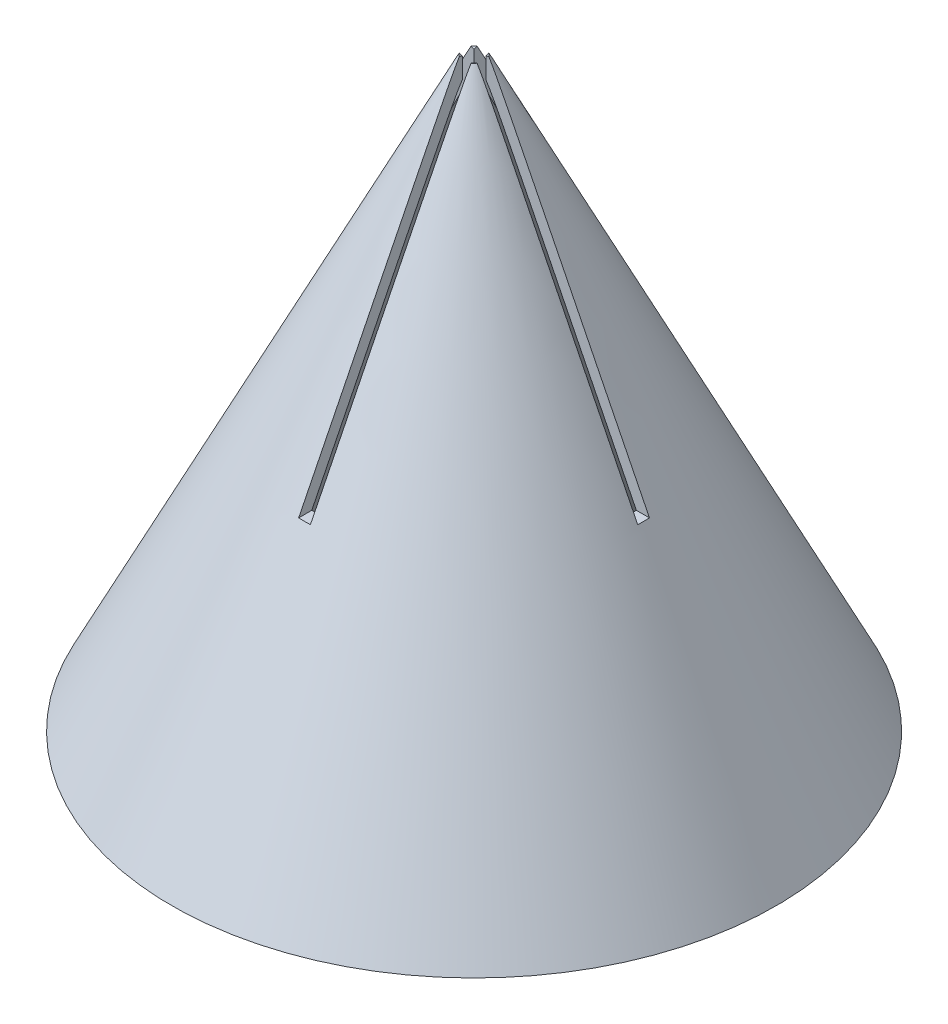
SolidWorks part; units mm, degrees
material "Thornel VCB-20 Carbon Cloth"
ref_plane "Front Plane" through (0, 0, 0) normal (0, 0, 1) x (1, 0, 0)
ref_plane "Top Plane" through (0, 0, 0) normal (0, 1, 0) x (1, 0, 0)
ref_plane "Right Plane" through (0, 0, 0) normal (1, 0, 0) x (0, 0, -1)
sketch "Sketch1" plane through (0, 0, 0) normal (0, 0, 1) x (1, 0, 0)
  line L1 (-22.25, 0.3849) -> (-0.7831, 43.5)
  line L4 (-0.7831, 43.5) -> (-0.01, 43.1151)
  line L5 (-0.01, 43.1151) -> (-21.4769, 0)
  line L6 (0, 0) -> (0, 9.1947) construction
  line L7 (-22.25, 0.3849) -> (-21.4769, 0)
  point P5 (0, 0)
  dimension "D1" = 0.8636
  dimension "D2" = 43.5
  dimension "D3" = 22.25
  dimension "D4" = 0.01
revolve "Revolve1" add sketch "Sketch1" angle 360 about L6
ref_plane "Plane1" through (0, 43.5, 0) normal (0, -1, 0) x (-1, 0, 0)
sketch "Sketch3" plane through (0, 43.5, 0) normal (0, -1, 0) x (-1, 0, 0)
  line L0 (-20.4318, -0.4318) -> (-20.4318, 0.4318)
  line L1 (-20.4318, 0.4318) -> (-0.4318, 0.4318)
  line L2 (-0.4318, 0.4318) -> (-0.4318, 20.4318)
  line L3 (-0.4318, 20.4318) -> (0.4318, 20.4318)
  line L4 (0.4318, 20.4318) -> (0.4318, 0.4318)
  line L5 (0.4318, 0.4318) -> (20.4318, 0.4318)
  line L6 (20.4318, 0.4318) -> (20.4318, -0.4318)
  line L7 (20.4318, -0.4318) -> (0.4318, -0.4318)
  line L8 (0.4318, -0.4318) -> (0.4318, -20.4318)
  line L9 (0.4318, -20.4318) -> (-0.4318, -20.4318)
  line L10 (-0.4318, -20.4318) -> (-0.4318, -0.4318)
  line L11 (-0.4318, -0.4318) -> (-20.4318, -0.4318)
  line L12 (-0.4318, -0.4318) -> (0.4318, 0.4318) construction
  line L13 (0.4318, -0.4318) -> (-0.4318, 0.4318) construction
  point P2 (0, 0)
  dimension "D1" = 0.8636
  dimension "D2" = 0.8636
  dimension "D3" = 20
extrude "Cut-Extrude1" cut sketch "Sketch3" along normal blind 23.5 contours L11 L0 L1 L2 L3 L4 L5 L6 L7 L8 L9 L10
